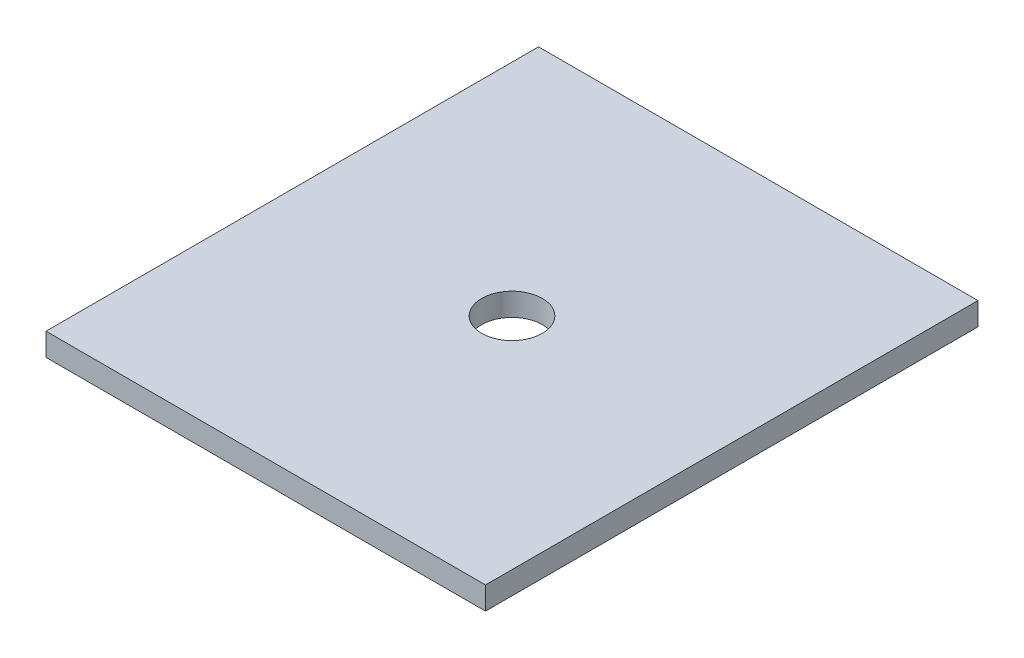
SolidWorks part; units mm, degrees
ref_plane "Front Plane" through (0, 0, 0) normal (0, 0, 1) x (1, 0, 0)
ref_plane "Top Plane" through (0, 0, 0) normal (0, 1, 0) x (1, 0, 0)
ref_plane "Right Plane" through (0, 0, 0) normal (1, 0, 0) x (0, 0, -1)
sketch "Sketch4" plane through (0, 0, 0) normal (0, 1, 0) x (1, 0, 0)
  line L0 (29, -32.5) -> (-29, -32.5)
  line L1 (29, 32.5) -> (29, -32.5)
  line L2 (-29, 32.5) -> (29, 32.5)
  line L3 (-29, -32.5) -> (-29, 32.5)
  circle A0 centre (0, 0) radius 4
  point P6 (0, 0)
  point P10 (2.2163, 1.4154)
  dimension "D5" = 8
  dimension "D1" = 32.5
  dimension "D2" = 65
  dimension "D3" = 58
  dimension "D4" = 29
extrude "Boss-Extrude1" add sketch "Sketch4" along normal blind 3
